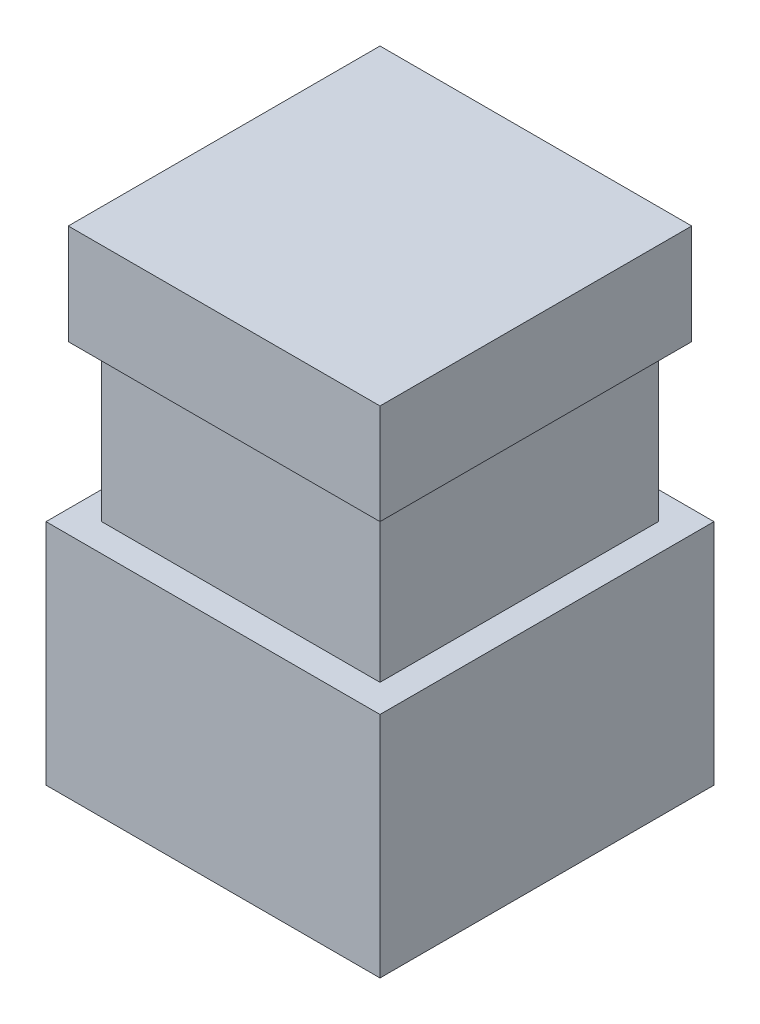
SolidWorks part; units mm, degrees
ref_plane "Front Plane" through (0, 0, 0) normal (0, 0, 1) x (1, 0, 0)
ref_plane "Top Plane" through (0, 0, 0) normal (0, 1, 0) x (1, 0, 0)
ref_plane "Right Plane" through (0, 0, 0) normal (1, 0, 0) x (0, 0, -1)
sketch "Sketch1" plane through (0, 0, 0) normal (0, 1, 0) x (1, 0, 0)
  line L1 (0, 0) -> (60, 0)
  line L2 (0, 0) -> (0, 60)
  line L3 (0, 60) -> (60, 60)
  line L4 (60, 0) -> (60, 60)
  dimension "D1" = 60
  dimension "D2" = 60
extrude "Boss-Extrude1" add sketch "Sketch1" along normal blind 41
hole_wizard "M3 Clearance Hole1" positions "Sketch3" profile "Sketch2" hole size "M3" standard "ANSI Metric"
sketch "Sketch3" plane through (0, 0, 0) normal (0, -1, 0) x (-1, 0, 0)
  line L0 (0, 60) -> (0, 0) construction
  line L1 (-60, 0) -> (-60, 60) construction
  line L2 (0, 0) -> (-60, 0) construction
  line L3 (-60, 60) -> (0, 60) construction
  point P0 (-3.5, 3.5)
  point P2 (-56.5, 3.5)
  point P4 (-56.5, 56.5)
  point P6 (-3.5, 56.5)
  dimension "D1" = 53
  dimension "D2" = 53
  dimension "D3" = 53
  dimension "D4" = 53
  dimension "D5" = 3.5
  dimension "D6" = 3.5
  dimension "D7" = 3.5
  dimension "D8" = 3.5
  dimension "D9" = 3.5
  dimension "D10" = 3.5
  dimension "D11" = 3.5
sketch "Sketch2" plane through (3.5, 0, -3.5) normal (1, 0, 0) x (0, 0, -1)
  line L0 (0, 0) -> (0, 8.0215)
  line L1 (0, 8.0215) -> (1.7, 7)
  line L2 (1.7, 7) -> (1.7, 0)
  line L5 (1.7, 0) -> (0, 0)
  line L10 (0, 8.0215) -> (-1.7, 7) construction
  line L11 (0, -6.35) -> (0, 107.95) construction
  dimension "Hole Dia." = 3.4
  dimension "Hole Depth" = 7
  dimension "Drill Angle" = 118
sketch "Sketch4" plane through (0, 41, 0) normal (0, 1, 0) x (1, 0, 0)
  line L0 (0, 60) -> (0, 0) construction
  line L1 (5, 5) -> (55, 5)
  line L2 (5, 5) -> (5, 55)
  line L3 (5, 55) -> (55, 55)
  line L4 (55, 5) -> (55, 55)
  line L5 (60, 0) -> (60, 60) construction
  line L6 (0, 0) -> (60, 0) construction
  line L7 (60, 60) -> (0, 60) construction
  dimension "D1" = 5
  dimension "D2" = 5
  dimension "D3" = 5
  dimension "D4" = 5
extrude "Boss-Extrude2" add sketch "Sketch4" along normal blind 28
sketch "Sketch5" plane through (0, 69, 0) normal (0, 1, 0) x (1, 0, 0)
  line L1 (58, 2) -> (2, 2)
  line L2 (58, 2) -> (58, 58)
  line L3 (58, 58) -> (2, 58)
  line L4 (2, 2) -> (2, 58)
  line L5 (5, 55) -> (5, 5) construction
  line L6 (55, 55) -> (5, 55) construction
  dimension "D1" = 56
  dimension "D2" = 56
  dimension "D3" = 3
  dimension "D4" = 3
extrude "Boss-Extrude3" add sketch "Sketch5" along normal blind 18
